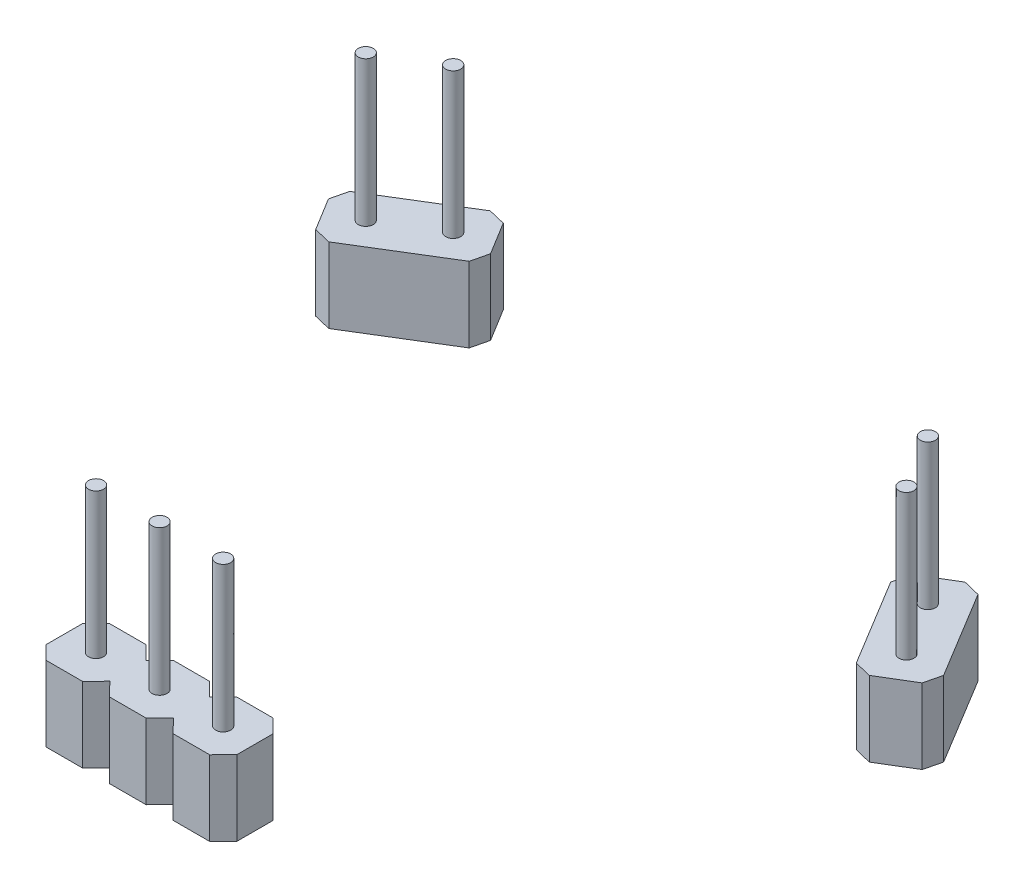
SolidWorks part; units mm, degrees
ref_plane "前视基准面" through (0, 0, 0) normal (0, 0, 1) x (1, 0, 0)
ref_plane "上视基准面" through (0, 0, 0) normal (0, 1, 0) x (1, 0, 0)
ref_plane "右视基准面" through (0, 0, 0) normal (1, 0, 0) x (0, 0, -1)
other "Configuration Table"
sketch "草图1" plane through (0, 3.5, 0) normal (0, 1, 0) x (1, 0, 0)
  line L0 (-951.6295, 285.452) -> (-951.6295, 1422.7853) construction
  line L1 (0, 0) -> (0, -17.25) construction
  line L2 (-1.27, -12.43) -> (-1.27, -14.97) construction
  line L3 (-3.81, -14.97) -> (3.81, -14.97)
  line L4 (-3.81, -14.97) -> (-3.81, -12.43)
  line L5 (-3.81, -12.43) -> (3.81, -12.43)
  line L6 (3.81, -14.97) -> (3.81, -12.43)
  line L7 (-3.81, -14.97) -> (3.81, -12.43) construction
  line L8 (-3.81, -12.43) -> (3.81, -14.97) construction
  line L9 (1.27, -12.98) -> (0.73, -12.43)
  line L10 (-1.81, -12.43) -> (-1.27, -12.98)
  line L11 (-1.27, -12.98) -> (-0.73, -12.43)
  line L12 (1.81, -12.43) -> (1.27, -12.98)
  line L13 (-3.81, -13.7) -> (3.81, -13.7) construction
  line L14 (1.81, -14.97) -> (1.27, -14.42)
  line L15 (1.27, -14.42) -> (0.73, -14.97)
  line L16 (-1.81, -14.97) -> (-1.27, -14.42)
  line L17 (-1.27, -14.42) -> (-0.73, -14.97)
  line L18 (-3.81, -12.98) -> (-3.27, -12.43)
  line L19 (-3.81, -14.42) -> (-3.27, -14.97)
  line L20 (3.81, -14.42) -> (3.27, -14.97)
  line L21 (3.81, -12.98) -> (3.27, -12.43)
  line L22 (12.8138, 6.3571) -> (15.4464, 2.0125)
  line L23 (15.4464, 2.0125) -> (13.2741, 0.6962)
  line L24 (13.2741, 0.6962) -> (10.6415, 5.0408)
  line L25 (10.6415, 5.0408) -> (12.8138, 6.3571)
  line L26 (11.9578, 2.8685) -> (14.1301, 4.1848) construction
  line L27 (-12.5259, 4.8989) -> (-8.1956, 7.5548)
  line L28 (-8.1956, 7.5548) -> (-9.5235, 9.72)
  line L29 (-9.5235, 9.72) -> (-13.8539, 7.064)
  line L30 (-13.8539, 7.064) -> (-12.5259, 4.8989)
  circle A0 centre (0, 0) radius 17.25 construction
  point P8 (0, -13.7)
  point P47 (-8.1956, 7.5548)
  point P48 (0, 0)
  dimension "D15" = 5.08
  dimension "D1" = 2.54
  dimension "D2" = 7.62
  dimension "D3" = 13.7
  dimension "D4" = 2.54
  dimension "D5" = 0.54
  dimension "D6" = 0.54
  dimension "D7" = 0.55
  dimension "D8" = 0.55
  dimension "D9" = 0.54
  dimension "D10" = 5.08
  dimension "D11" = 2.54
  dimension "D12" = 10.6415
  dimension "D13" = 0.6962
  dimension "D14" = 4.8049
  dimension "D16" = 2.54
  dimension "D17" = 8.1956
  dimension "D18" = 4.8989
  dimension "D19" = 4.3304
extrude "凸台-拉伸1" add sketch "草图1" against normal up to surface (3 mm away) contours L6 L21 L5 L12 L9 L11 L10 L18 L4 L19 L3 L16 L17 L15 L14 L20 | L29 L30 L27 L28 | L25 L24 L23 L22
chamfer "倒角1" distance 0.5 angle 45 4 edges at (-8.1956, 2, -7.5548) (-12.5259, 2, -4.8989) (-13.8539, 2, -7.064) (-9.5235, 2, -9.72)
chamfer "倒角2" distance 0.5 angle 45 4 edges at (15.4464, 2, -2.0125) (13.2741, 2, -0.6962) (10.6415, 2, -5.0408) (12.8138, 2, -6.3571)
sketch "草图2" plane through (0, 3.5, 0) normal (0, 1, 0) x (1, 0, 0)
  line L0 (-13.1899, 5.9815) -> (-8.8595, 8.6374) construction
  line L1 (-13.5925, 6.6378) -> (-12.7874, 5.3251) construction
  line L2 (-8.457, 7.981) -> (-9.2621, 9.2938) construction
  line L3 (11.7277, 5.699) -> (14.3603, 1.3543) construction
  line L4 (11.0691, 5.2999) -> (12.3862, 6.098) construction
  line L5 (15.0188, 1.7534) -> (13.7017, 0.9553) construction
  line L6 (-3.81, -13.7) -> (3.81, -13.7) construction
  line L7 (-3.81, -14.42) -> (-3.81, -12.98) construction
  line L8 (3.81, -14.42) -> (3.81, -12.98) construction
  circle A0 centre (-12.1073, 6.6454) radius 0.3
  circle A1 centre (-9.9421, 7.9734) radius 0.3
  circle A2 centre (12.3858, 4.6128) radius 0.3
  circle A3 centre (13.7021, 2.4405) radius 0.3
  circle A4 centre (0, -13.7) radius 0.3
  circle A5 centre (-2.54, -13.7) radius 0.3
  circle A6 centre (2.54, -13.7) radius 0.3
  point P10 (-11.0247, 7.3094)
  point P21 (13.044, 3.5267)
  point P34 (0, 0)
  point P35 (0, 0)
  point P36 (-1.6729, -14.4126)
  dimension "D1" = 0.6
  dimension "D2" = 0.6
  dimension "D7" = 0.6
  dimension "D8" = 0.6
  dimension "D9" = 0.6
  dimension "D10" = 0.6
  dimension "D11" = 0.6
  dimension "D3" = 1.27
  dimension "D4" = 1.27
  dimension "D5" = 1.27
  dimension "D6" = 1.27
  dimension "D12" = 2.54
  dimension "D13" = 2.54
extrude "凸台-拉伸2" add sketch "草图2" along normal blind 5.8
